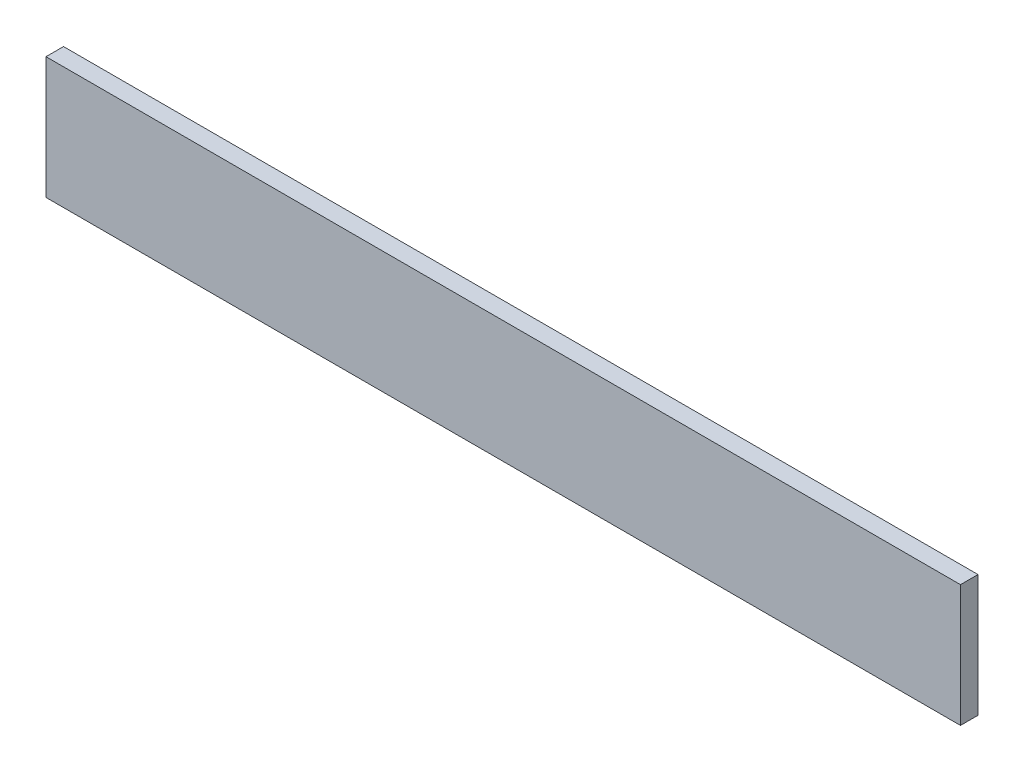
SolidWorks part; units mm, degrees
material "Pine"
ref_plane "Front Plane" through (0, 0, 0) normal (0, 0, 1) x (1, 0, 0)
ref_plane "Top Plane" through (0, 0, 0) normal (0, 1, 0) x (1, 0, 0)
ref_plane "Right Plane" through (0, 0, 0) normal (1, 0, 0) x (0, 0, -1)
sketch "Sketch1" plane through (0, 0, 0) normal (0, 0, 1) x (1, 0, 0)
  line L1 (-476.25, 63.5) -> (476.25, 63.5)
  line L2 (-476.25, 63.5) -> (-476.25, -63.5)
  line L3 (-476.25, -63.5) -> (476.25, -63.5)
  line L4 (476.25, 63.5) -> (476.25, -63.5)
  line L5 (-476.25, 63.5) -> (476.25, -63.5) construction
  line L6 (-476.25, -63.5) -> (476.25, 63.5) construction
  point P0 (0, 0)
  dimension "D1" = 952.5
  dimension "D2" = 127
extrude "Boss-Extrude1" add sketch "Sketch1" along normal blind 18.2562
